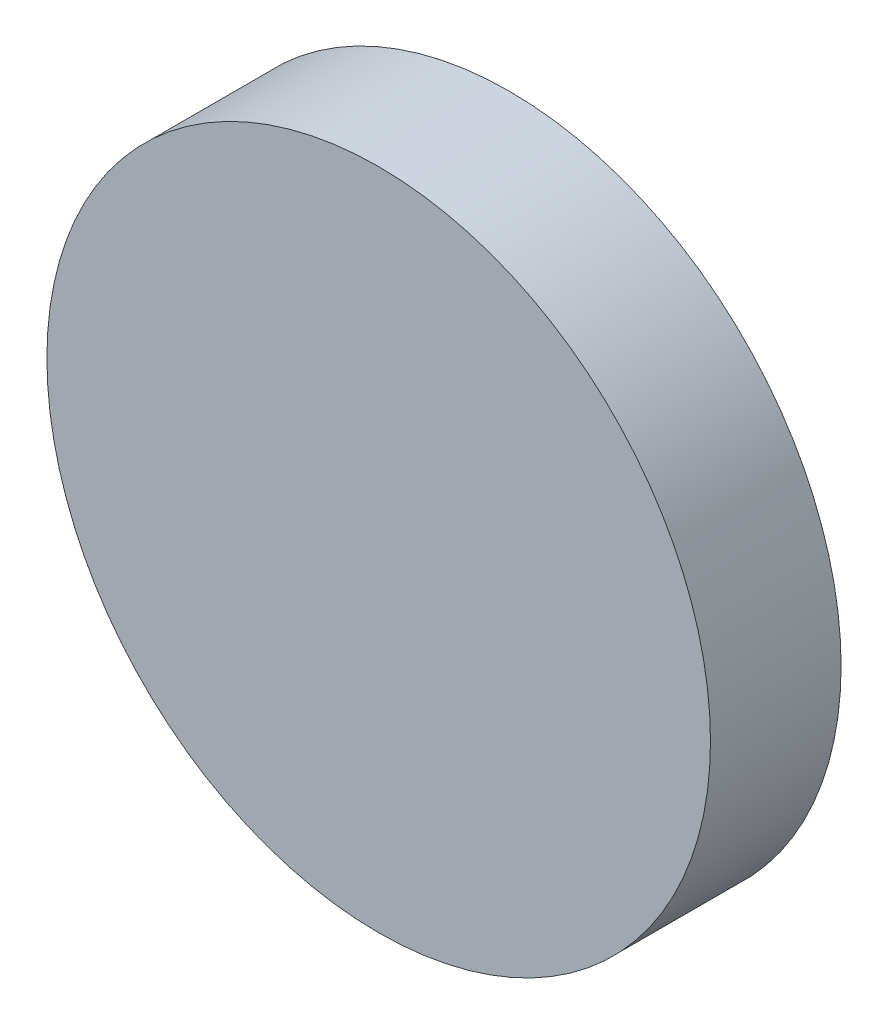
SolidWorks part; units mm, degrees
material "1060 Legierung"
ref_plane "Ebene vorne" through (0, 0, 0) normal (1, 0, 0) x (0, 1, 0)
ref_plane "Ebene oben" through (0, 0, 0) normal (0, 0, 1) x (0, 1, 0)
ref_plane "Ebene rechts" through (0, 0, 0) normal (0, 1, 0) x (-1, 0, 0)
sketch "Skizze1" plane through (0, 0, 0) normal (0, 0, 1) x (0, 1, 0)
  circle A0 centre (0, 0) radius 12.7
extrude "Aufsatz-Linear austragen1" add sketch "Skizze1" along normal blind 5
sketch "Skizze2" plane through (0, 0, 0) normal (0, 0, 1) x (0, 1, 0)
  circle A0 centre (0, 0) radius 6
extrude "Aufsatz-Linear austragen3" add sketch "Skizze2" against normal blind 4.2
